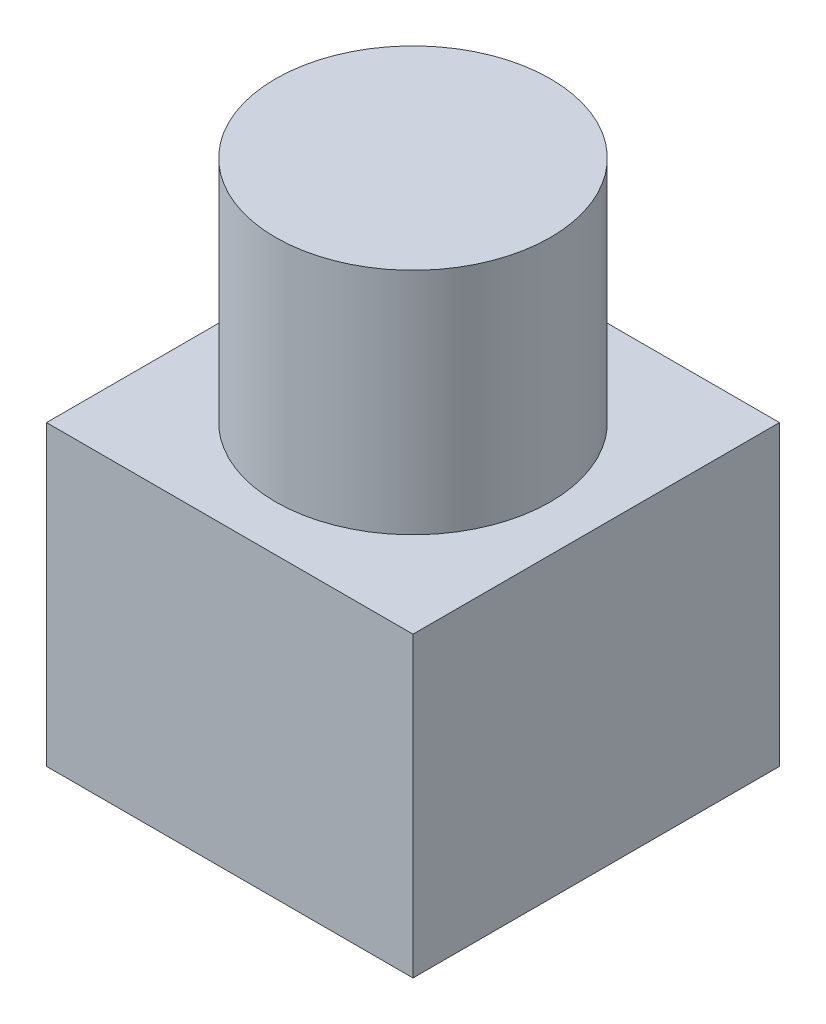
SolidWorks part; units mm, degrees
ref_plane "Płaszczyzna przednia" through (0, 0, 0) normal (0, 0, 1) x (1, 0, 0)
ref_plane "Płaszczyzna górna" through (0, 0, 0) normal (0, 1, 0) x (1, 0, 0)
ref_plane "Płaszczyzna prawa" through (0, 0, 0) normal (1, 0, 0) x (0, 0, -1)
sketch "Szkic1" plane through (0, 0, 0) normal (0, 1, 0) x (1, 0, 0)
  line L1 (-4, -4) -> (4, -4)
  line L2 (-4, -4) -> (-4, 4)
  line L3 (-4, 4) -> (4, 4)
  line L4 (4, -4) -> (4, 4)
  line L5 (-4, -4) -> (4, 4) construction
  line L6 (-4, 4) -> (4, -4) construction
  point P0 (0, 0)
  dimension "D1" = 8
extrude "Dodanie-wyciągnięcie1" add sketch "Szkic1" along normal blind 6.5
sketch "Szkic2" plane through (0, 6.5, 0) normal (0, 1, 0) x (1, 0, 0)
  circle A0 centre (0, 0) radius 3
  dimension "D1" = 6
extrude "Dodanie-wyciągnięcie2" add sketch "Szkic2" along normal blind 5
